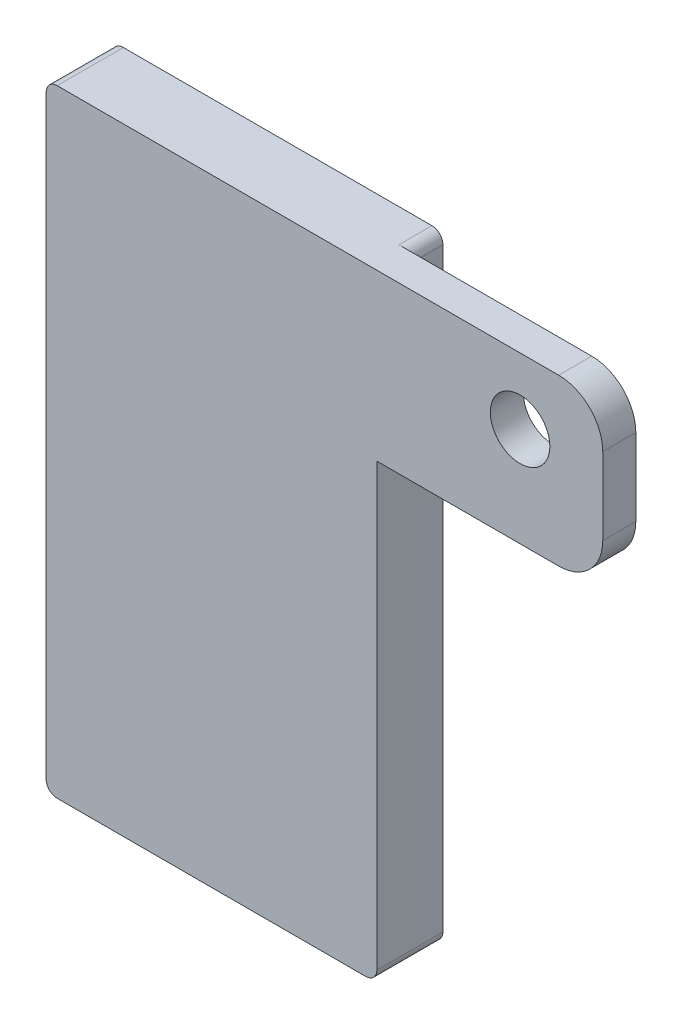
SolidWorks part; units mm, degrees
ref_plane "Front Plane" through (0, 0, 0) normal (0, 0, 1) x (1, 0, 0)
ref_plane "Top Plane" through (0, 0, 0) normal (0, 1, 0) x (1, 0, 0)
ref_plane "Right Plane" through (0, 0, 0) normal (1, 0, 0) x (0, 0, -1)
sketch "Sketch1" plane through (0, 0, 0) normal (0, 0, 1) x (1, 0, 0)
  line L0 (0, 0) -> (0, 56)
  line L3 (0, 56) -> (50.5, 56)
  line L4 (50.5, 56) -> (50.5, 41)
  line L5 (50.5, 41) -> (30, 41)
  line L6 (30, 41) -> (30, 0)
  line L7 (30, 0) -> (0, 0)
  circle A0 centre (43, 50) radius 2.7
  dimension "D7" = 5.4
  dimension "D1" = 30
  dimension "D2" = 20.5
  dimension "D3" = 15
  dimension "D4" = 41
  dimension "D5" = 7.5
  dimension "D6" = 6
extrude "Boss-Extrude1" add sketch "Sketch1" along normal blind 3
sketch "Sketch2" plane through (0, 0, 0) normal (0, 0, -1) x (-1, 0, 0)
  line L1 (-30, 0) -> (0, 0)
  line L2 (-30, 0) -> (-30, 56)
  line L3 (-30, 56) -> (0, 56)
  line L4 (0, 0) -> (0, 56)
  line L5 (-25, 51) -> (-5, 51)
  line L6 (-25, 51) -> (-25, 5)
  line L7 (-25, 5) -> (-5, 5)
  line L8 (-5, 51) -> (-5, 5)
  dimension "D1" = 5
  dimension "D2" = 5
  dimension "D3" = 5
  dimension "D4" = 5
extrude "Boss-Extrude2" add sketch "Sketch2" along normal blind 3
fillet "Fillet1" radius 4 2 edges at (50.5, 41, 1.5) (50.5, 56, 1.5)
fillet "Fillet3" radius 1 4 edges at (30, 56, -1.5) (0, 56, 0) (0, 0, 0) (30, 0, 0)
